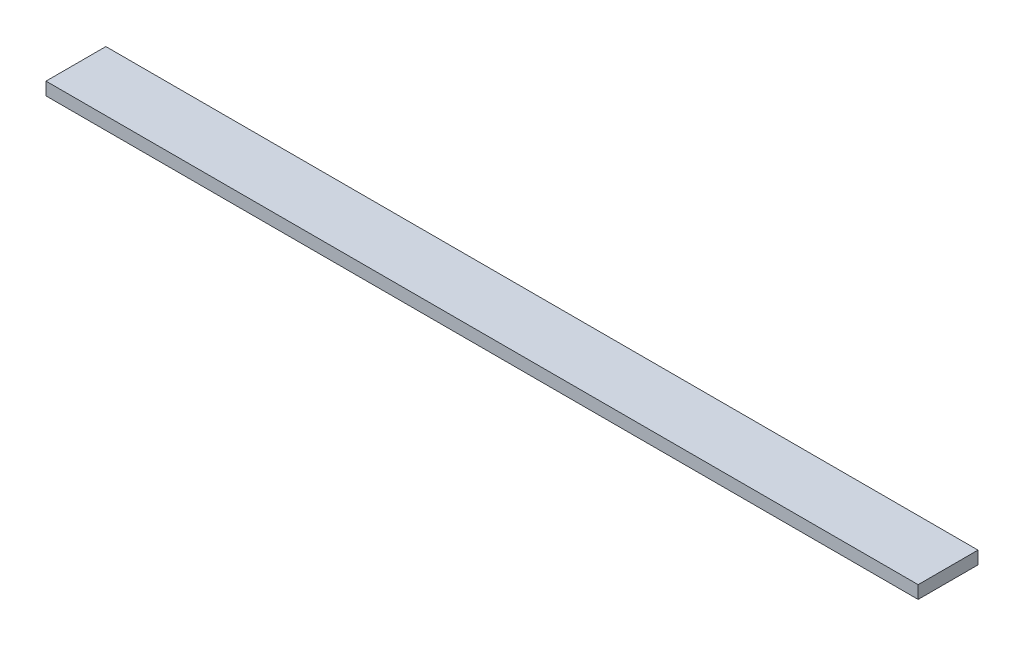
SolidWorks part; units mm, degrees
ref_plane "Front Plane" through (0, 0, 0) normal (0, 0, 1) x (1, 0, 0)
ref_plane "Top Plane" through (0, 0, 0) normal (0, 1, 0) x (1, 0, 0)
ref_plane "Right Plane" through (0, 0, 0) normal (1, 0, 0) x (0, 0, -1)
other "Configuration Table"
sketch "Sketch1" plane through (0, 0, 0) normal (0, 0, 1) x (1, 0, 0)
  line L1 (130, 140) -> (640, 140)
  line L2 (130, 140) -> (130, 147.5)
  line L3 (130, 147.5) -> (640, 147.5)
  line L4 (640, 140) -> (640, 147.5)
extrude "OVEN_pano_klemens_rayi_1" add sketch "Sketch1" against normal blind 35 from offset 213 separate body
